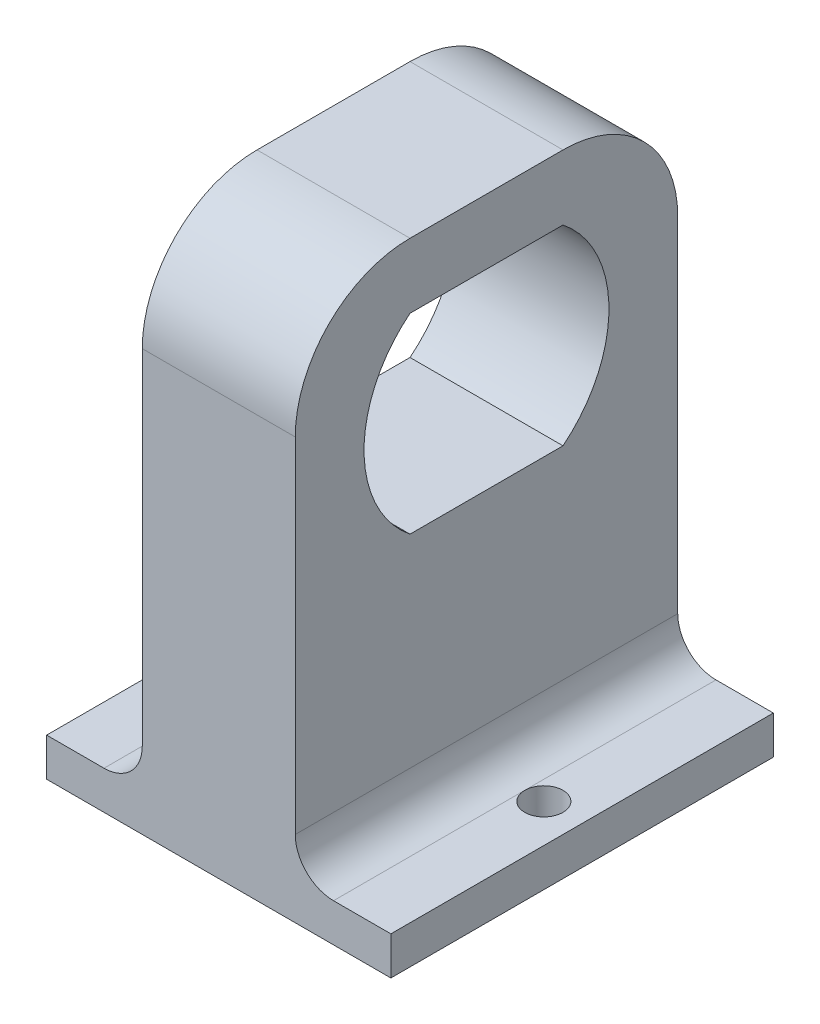
SolidWorks part; units mm, degrees
material "ABS"
ref_plane "Front Plane" through (0, 0, 0) normal (0, 0, 1) x (1, 0, 0)
ref_plane "Top Plane" through (0, 0, 0) normal (0, 1, 0) x (1, 0, 0)
ref_plane "Right Plane" through (0, 0, 0) normal (1, 0, 0) x (0, 0, -1)
sketch "Sketch1" plane through (0, 0, 0) normal (1, 0, 0) x (0, 0, -1)
  line L0 (0, -44.45) -> (0, 17.78) construction
  line L1 (-31.75, -44.45) -> (31.75, -44.45)
  line L2 (-31.75, -44.45) -> (-31.75, 44.45)
  line L3 (-31.75, 44.45) -> (31.75, 44.45)
  line L4 (31.75, -44.45) -> (31.75, 44.45)
  line L5 (-31.75, -44.45) -> (31.75, 44.45) construction
  line L6 (-31.75, 44.45) -> (31.75, -44.45) construction
  line L12 (-12.7, 1.905) -> (12.7, 1.905)
  line L14 (-12.7, 33.655) -> (12.7, 33.655)
  line L16 (-12.7, 1.905) -> (12.7, 33.655) construction
  line L17 (-12.7, 33.655) -> (12.7, 1.905) construction
  arc A0 (-12.7, 33.655) -> (-12.7, 1.905) centre (0, 17.78) ccw
  arc A1 (12.7, 1.905) -> (12.7, 33.655) centre (0, 17.78) ccw
  point P0 (0, 0)
  dimension "D1" = 88.9
  dimension "D2" = 63.5
  dimension "D3" = 62.23
  dimension "D4" = 25.4
  dimension "D5" = 31.75
extrude "Boss-Extrude1" add sketch "Sketch1" along normal mid plane 25.4
sketch "Sketch2" plane through (0, 0, 0) normal (1, 0, 0) x (0, 0, -1)
  line L0 (31.75, -44.45) -> (31.75, 44.45) construction
  line L1 (-31.75, -44.45) -> (31.75, -44.45)
  line L2 (-31.75, -44.45) -> (-31.75, -38.1)
  line L3 (-31.75, -38.1) -> (31.75, -38.1)
  line L4 (31.75, -44.45) -> (31.75, -38.1)
  dimension "D1" = 6.35
extrude "Boss-Extrude2" add sketch "Sketch2" along normal mid plane 57.15
fillet "Fillet1" radius 6.35 2 edges at (-12.7, -38.1, 0) (12.7, -38.1, 0)
sketch "Sketch3" plane through (0, -38.1, 0) normal (0, 1, 0) x (1, 0, 0)
  line L1 (28.575, 31.75) -> (28.575, -31.75) construction
  line L3 (-53.5691, 0) -> (53.5691, 0) construction
  circle A0 centre (22.225, 0) radius 3.175
  point P2 (0, 0)
  dimension "D1" = 6.35
  dimension "D3" = 6.35
extrude "Cut-Extrude1" cut sketch "Sketch3" against normal through all
mirror "Mirror1" about plane through (0, 0, 0) normal (1, 0, 0) of "Cut-Extrude1"
fillet "Fillet2" radius 19.05 2 edges at (0, 44.45, -31.75) (0, 44.45, 31.75)
